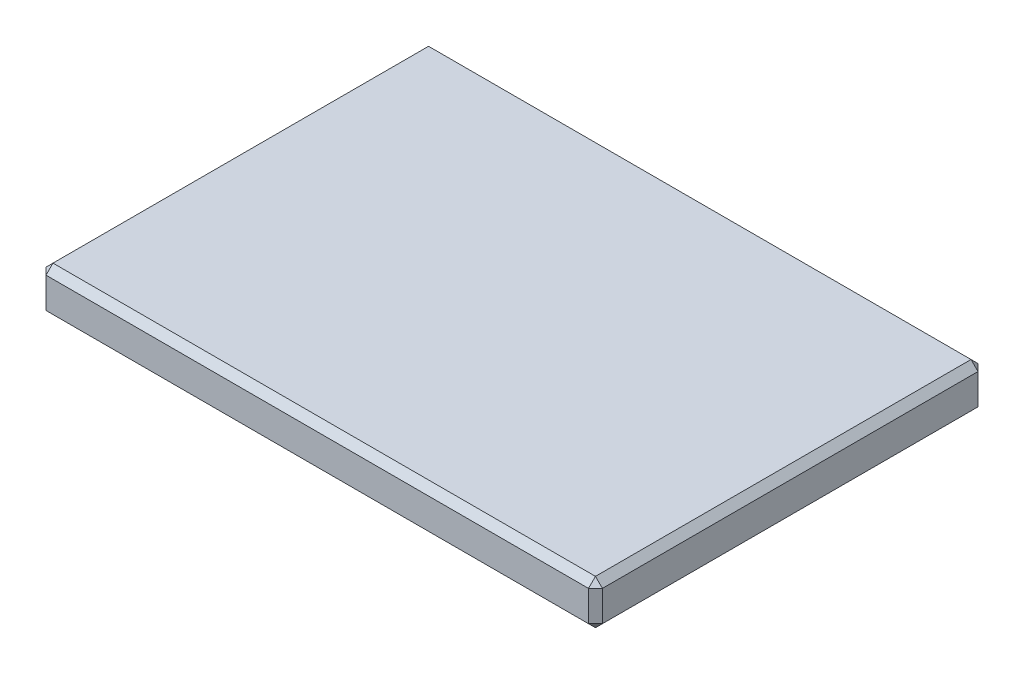
SolidWorks part; units mm, degrees
ref_plane "Front Plane" through (0, 0, 0) normal (0, 0, 1) x (1, 0, 0)
ref_plane "Top Plane" through (0, 0, 0) normal (0, 1, 0) x (1, 0, 0)
ref_plane "Right Plane" through (0, 0, 0) normal (1, 0, 0) x (0, 0, -1)
sketch "Sketch1" plane through (0, 0, 0) normal (0, 1, 0) x (1, 0, 0)
  line L1 (0, 0) -> (40, 0)
  line L2 (0, 0) -> (0, 28)
  line L3 (0, 28) -> (40, 28)
  line L4 (40, 0) -> (40, 28)
  dimension "D1" = 28
  dimension "D2" = 40
extrude "Boss-Extrude1" add sketch "Sketch1" along normal blind 3.2
chamfer "Chamfer1" distance 0.5 angle 45 12 edges at (40, 1.6, 0) (0, 1.6, 0) (40, 1.6, -28) (20, 0, 0) (40, 0, -14) (20, 0, -28) (0, 0, -14) (0, 1.6, -28) (20, 3.2, -28) (40, 3.2, -14) (20, 3.2, 0) (0, 3.2, -14)
